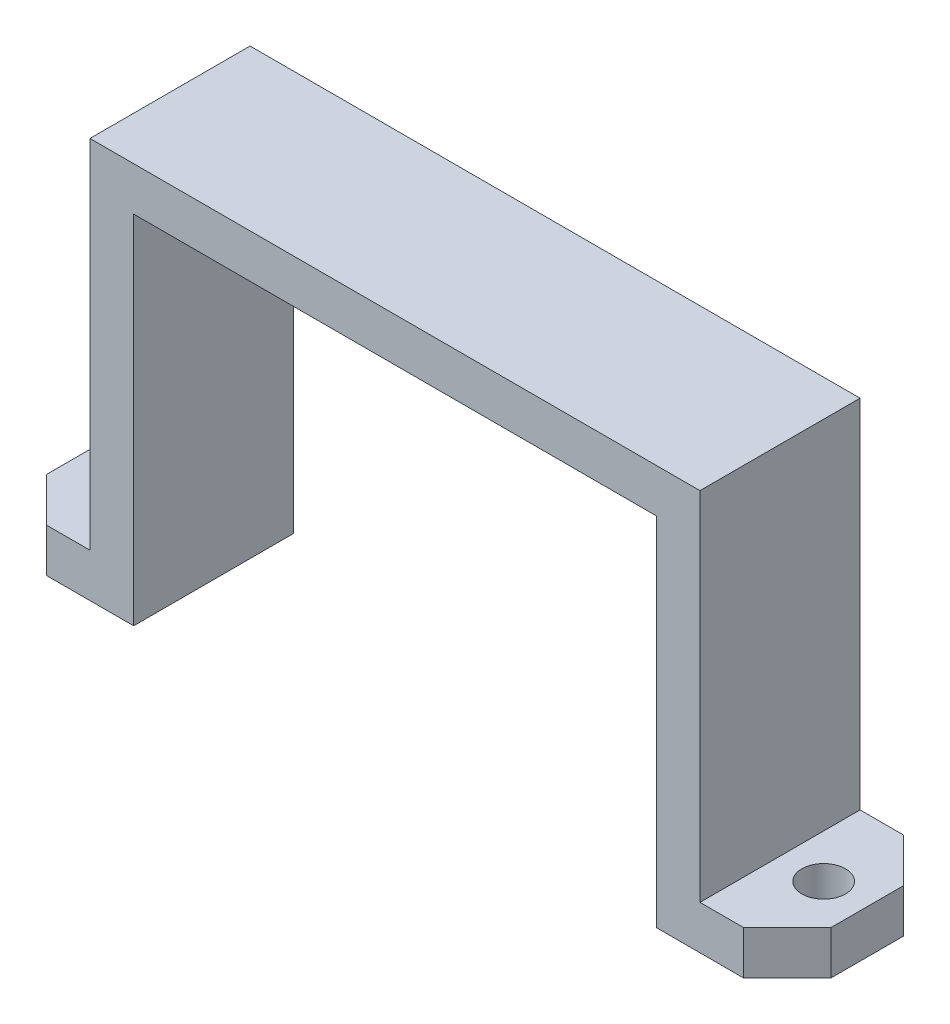
SolidWorks part; units mm, degrees
ref_plane "Front Plane" through (0, 0, 0) normal (0, 0, 1) x (1, 0, 0)
ref_plane "Top Plane" through (0, 0, 0) normal (0, 1, 0) x (1, 0, 0)
ref_plane "Right Plane" through (0, 0, 0) normal (1, 0, 0) x (0, 0, -1)
sketch "Sketch1" plane through (0, 0, 0) normal (0, 0, 1) x (1, 0, 0)
  line L0 (-26.955, 0) -> (-17.955, 0)
  line L1 (-17.955, 0) -> (-17.955, 24.5)
  line L2 (-17.955, 24.5) -> (17.955, 24.5)
  line L3 (0, 24.5) -> (0, 39.5072) construction
  line L4 (20.955, 27.5) -> (-20.955, 27.5)
  line L5 (-20.955, 27.5) -> (-20.955, 3)
  line L6 (-20.955, 3) -> (-26.955, 3)
  line L7 (-26.955, 3) -> (-26.955, 0)
  line L8 (26.955, 3) -> (26.955, 0)
  line L9 (20.955, 3) -> (26.955, 3)
  line L10 (20.955, 27.5) -> (20.955, 3)
  line L11 (17.955, 0) -> (17.955, 24.5)
  line L12 (26.955, 0) -> (17.955, 0)
  point P12 (0, 27.5)
  dimension "D1" = 24.5
  dimension "D2" = 3
  dimension "D3" = 3
  dimension "D4" = 17.955
  dimension "D5" = 6
  dimension "D6" = 3
extrude "Boss-Extrude1" add sketch "Sketch1" along normal blind 11
chamfer "Chamfer1" distance 3 angle 45 4 edges at (26.955, 1.5, 0) (26.955, 1.5, 11) (-26.955, 1.5, 0) (-26.955, 1.5, 11)
sketch "Sketch2" plane through (0, 3, 0) normal (0, 1, 0) x (1, 0, 0)
  line L0 (-26.955, -8) -> (-26.955, -3) construction
  line L2 (0, -6.05) -> (0, 6.05) construction
  circle A0 centre (-23.955, -5.5) radius 1.5
  circle A1 centre (23.955, -5.5) radius 1.5
  dimension "D2" = 3
  dimension "D1" = 3
extrude "Cut-Extrude1" cut sketch "Sketch2" against normal through all
